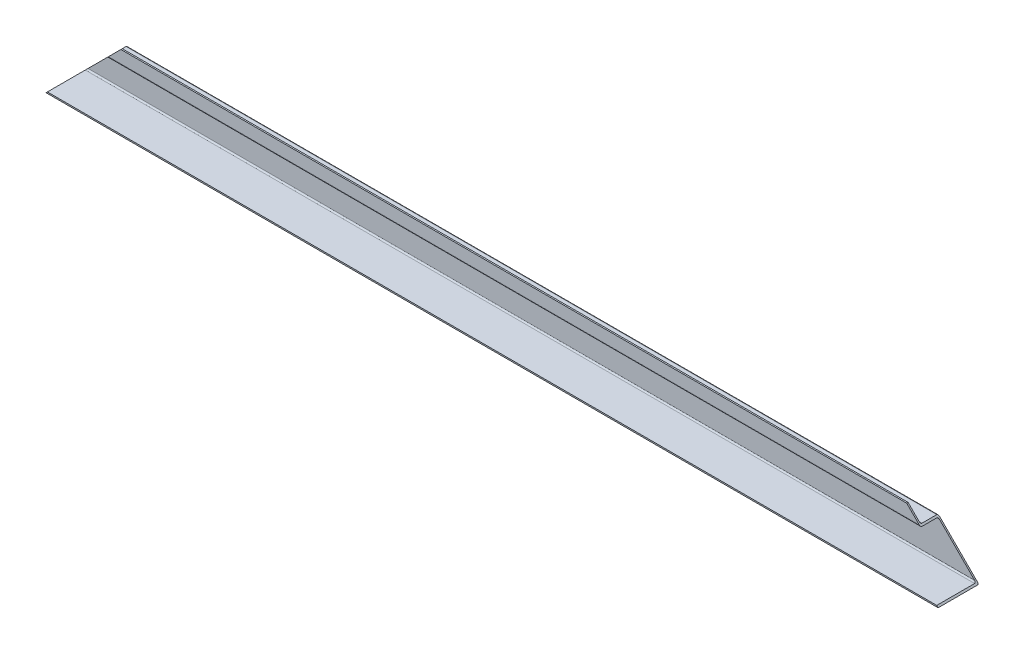
SolidWorks part; units mm, degrees
ref_plane "Front Plane" through (0, 0, 0) normal (0, 0, 1) x (1, 0, 0)
ref_plane "Top Plane" through (0, 0, 0) normal (0, 1, 0) x (1, 0, 0)
ref_plane "Right Plane" through (0, 0, 0) normal (1, 0, 0) x (0, 0, -1)
sketch "Sketch1" plane through (0, 0, 0) normal (1, 0, 0) x (0, 0, -1)
  line L0 (0, 0) -> (85, 0)
  line L1 (85, 0) -> (85, 82)
  line L2 (85, 82) -> (47, 82)
  line L3 (47, 82) -> (47, 112)
  line L4 (0, -3) -> (88, -3)
  line L5 (88, -3) -> (88, 85)
  line L6 (88, 85) -> (50, 85)
  line L7 (50, 85) -> (50, 112)
  line L8 (47, 112) -> (50, 112)
  line L9 (0, 0) -> (0, -3)
  point P11 (48.5, 112)
  dimension "D1" = 3
  dimension "D2" = 27
  dimension "D3" = 38
  dimension "D4" = 88
  dimension "D5" = 88
extrude "Boss-Extrude1" add sketch "Sketch1" along normal blind 1930
fillet "Fillet1" radius 3 6 edges at (965, -3, -88) (965, 85, -88) (965, 85, -50) (965, 82, -85) (965, 0, -85) (965, 82, -47)
sketch "Sketch4" plane through (0, 0, -88) normal (0, 0, -1) x (-1, 0, 0)
  line L0 (-1930, -3) -> (-1815, 112)
  line L1 (-1930, 112) -> (0, 112) construction
  line L2 (-1815, 112) -> (-1930, 112)
  line L3 (-1930, 112) -> (-1930, -3)
  dimension "D1" = 45
extrude "Cut-Extrude1" cut sketch "Sketch4" against normal blind 88
sketch "Sketch5" plane through (0, 0, -88) normal (0, 0, -1) x (-1, 0, 0)
  line L0 (0, -3) -> (-115, 112)
  line L1 (-1815, 112) -> (0, 112) construction
  line L2 (-115, 112) -> (0, 112)
  line L3 (0, 85) -> (0, 112) construction
  line L4 (0, 112) -> (0, -3)
  dimension "D1" = 45
extrude "Cut-Extrude2" cut sketch "Sketch5" against normal blind 88
equation "\"D1@Boss-Extrude1\" = \"boxWidth\""
equation "\"CarBeamWidth\"=700.0"
equation "\"WheelWidth\"=650.0"
equation "\"Wheel_FrontBoxDistance\"=1390.0"
equation "\"boxLength\"=5100.0"
equation "\"boxWidth\"=1930.0"
equation "\"MetalSheet_3mm_length\"=5030.0"
equation "\"MetalSheet_3mm_width\"=1923.0"
equation "\"MetalSheet_3mm_FloorCut_L_length\"=1764.0"
equation "\"MetalSheet_3mm_FloorCut_L_disdance\"=1665.0"
equation "\"MetalSheet_3mm_FloorCut_R_length\"=1764.0"
equation "\"MetalSheet_3mm_FloorCut_R_disdance\"=1665.0"
equation "\"indoorHeight\"=1940.0"
equation "\"indoorHeight_para\"=25.0"
equation "\"rearLightHeight_para\"=265.0"
equation "\"haveDoor_R\"=1"
equation "\"side_door_bottom_R_3mm_length\"=1934.0"
equation "\"side_door_bottom_R_3mm_toFrontDistance\"=1583.0"
equation "\"1Bar_Side_RF_3mm_length\"=1493.0"
equation "\"1Bar_Side_RB_3mm_length\"=1493.0"
equation "\"DoorSeparator_RF_3mm_withHinge_toFrontDistance\"=1673.0"
equation "\"DoorSeparator_RF_3mm_withHinge_exist\"=1"
equation "\"DoorSeparator_RB_3mm_withHinge_toFrontDistance\"=3427.0"
equation "\"DoorSeparator_RB_3mm_withHinge_exist\"=1"
equation "\"Door_R1_L_open_Single_toFrontDistance\"=2547.5"
equation "\"Door_R1_L_open_Single_exist\"=1"
equation "\"door_base_long7_R1_L_open_Single_height\"=1890.0"
equation "\"door_base_short7_R1_L_open_Single_height\"=1890.0"
equation "\"door_base_short7_R1_L_open_Single_width\"=864"
equation "\"Door_R1_R_open_Single_toFrontDistance\"=3422.0"
equation "\"Door_R1_R_open_Single_exist\"=1"
equation "\"door_base_long7_R1_R_open_Single_height\"=1890.0"
equation "\"door_base_short7_R1_R_open_Single_height\"=1890.0"
equation "\"door_base_short7_R1_R_open_Single_width\"=864"
equation "\"x\"=66.0"
equation "\"da\"=62.0"
equation "\"SquareTube_length\"=1923.0"
equation "\"channelSteel_length\"=5030.0"
equation "\"SquareTube_inFront_AvgDistance\"=285.0"
equation "\"SquareTube_inFront_TotalCount\"=5"
equation "\"SquareTube_inFront1_cutDepth50_R\"=0.5"
equation "\"SquareTube_inFront1_cutDepth50_L\"=0.5"
equation "\"SquareTube_inFront2_cutDepth50_R\"=0.5"
equation "\"SquareTube_inFront2_cutDepth50_L\"=0.5"
equation "\"SquareTube_inFront3_cutDepth50_R\"=0.5"
equation "\"SquareTube_inFront3_cutDepth50_L\"=0.5"
equation "\"SquareTube_inFront4_cutDepth50_R\"=0.5"
equation "\"SquareTube_inFront4_cutDepth50_L\"=0.5"
equation "\"SquareTube_inFront5_cutDepth50_R\"=50"
equation "\"SquareTube_inFront5_cutDepth50_L\"=50"
equation "\"SquareTube_inFront6_cutDepth50_R\"=50"
equation "\"SquareTube_inFront6_cutDepth50_L\"=50"
equation "\"SquareTube_inFront7_cutDepth50_R\"=50"
equation "\"SquareTube_inFront7_cutDepth50_L\"=50"
equation "\"SquareTube_inFront8_cutDepth50_R\"=50"
equation "\"SquareTube_inFront8_cutDepth50_L\"=50"
equation "\"SquareTube_inFront9_cutDepth50_R\"=50"
equation "\"SquareTube_inFront9_cutDepth50_L\"=50"
equation "\"SquareTube_inFront10_cutDepth50_R\"=50"
equation "\"SquareTube_inFront10_cutDepth50_L\"=50"
equation "\"SquareTube_inFront11_cutDepth50_R\"=50"
equation "\"SquareTube_inFront11_cutDepth50_L\"=50"
equation "\"SquareTube_inFront12_cutDepth50_R\"=50"
equation "\"SquareTube_inFront12_cutDepth50_L\"=50"
equation "\"SquareTube_inFront13_cutDepth50_R\"=50"
equation "\"SquareTube_inFront13_cutDepth50_L\"=50"
equation "\"SquareTube_inFront14_cutDepth50_R\"=50"
equation "\"SquareTube_inFront14_cutDepth50_L\"=50"
equation "\"SquareTube_inBack_AvgDistance\"=333.125"
equation "\"SquareTube_inBack_TotalCount\"=9"
equation "\"SquareTube_inBack1_cutDepth50_R\"=50"
equation "\"SquareTube_inBack1_cutDepth50_L\"=50"
equation "\"SquareTube_inBack2_cutDepth50_R\"=50"
equation "\"SquareTube_inBack2_cutDepth50_L\"=50"
equation "\"SquareTube_inBack3_cutDepth50_R\"=50"
equation "\"SquareTube_inBack3_cutDepth50_L\"=50"
equation "\"SquareTube_inBack4_cutDepth50_R\"=50"
equation "\"SquareTube_inBack4_cutDepth50_L\"=50"
equation "\"SquareTube_inBack5_cutDepth50_R\"=50"
equation "\"SquareTube_inBack5_cutDepth50_L\"=50"
equation "\"SquareTube_inBack6_cutDepth50_R\"=0.5"
equation "\"SquareTube_inBack6_cutDepth50_L\"=0.5"
equation "\"SquareTube_inBack7_cutDepth50_R\"=0.5"
equation "\"SquareTube_inBack7_cutDepth50_L\"=0.5"
equation "\"SquareTube_inBack8_cutDepth50_R\"=0.5"
equation "\"SquareTube_inBack8_cutDepth50_L\"=0.5"
